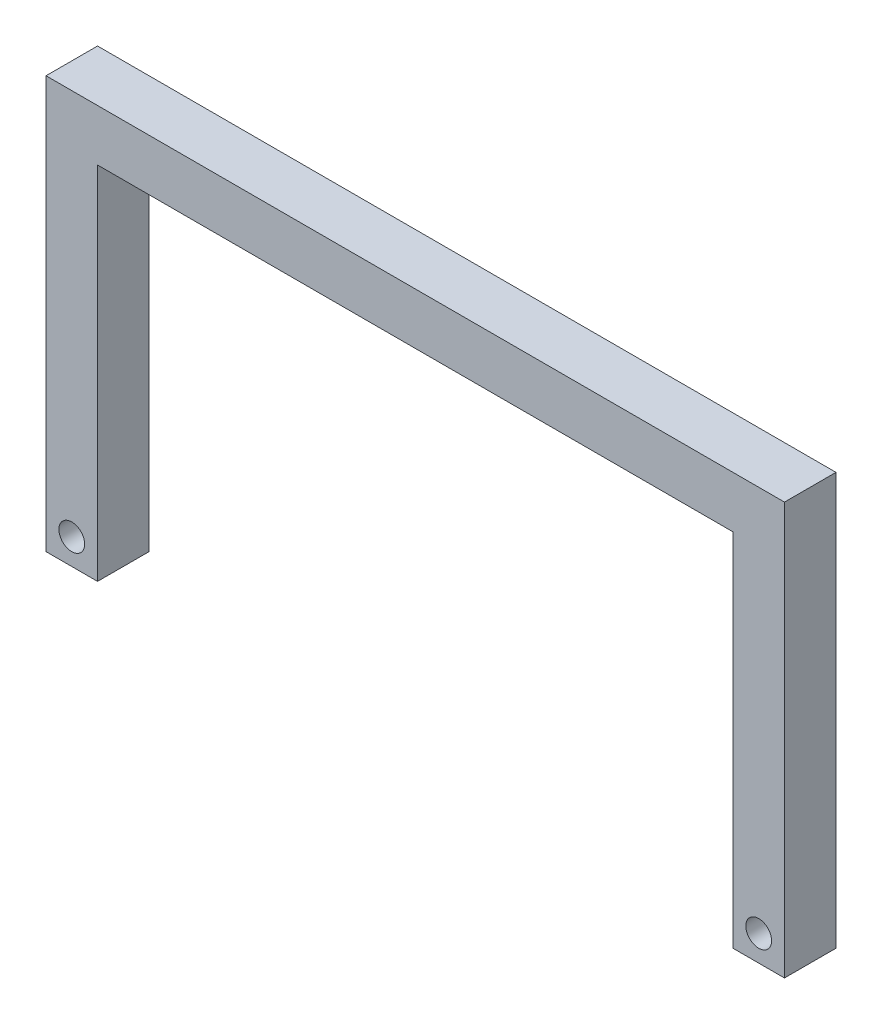
SolidWorks part; units mm, degrees
ref_plane "Front Plane" through (0, 0, 0) normal (0, 0, 1) x (1, 0, 0)
ref_plane "Top Plane" through (0, 0, 0) normal (0, 1, 0) x (1, 0, 0)
ref_plane "Right Plane" through (0, 0, 0) normal (1, 0, 0) x (0, 0, -1)
sketch "Sketch1" plane through (0, 0, 0) normal (0, 0, 1) x (1, 0, 0)
  line L0 (-185, -15) -> (-185, -225)
  line L1 (215, 15) -> (-215, 15)
  line L2 (215, 15) -> (215, -15)
  line L4 (-215, 15) -> (-215, -15)
  line L5 (215, 15) -> (-215, -15) construction
  line L6 (215, -15) -> (-215, 15) construction
  line L8 (-215, 15) -> (-215, -225)
  line L9 (-215, -225) -> (-185, -225)
  line L12 (215, 15) -> (215, -225)
  line L13 (215, -225) -> (185, -225)
  line L15 (185, -15) -> (185, -225)
  line L16 (185, -15) -> (-185, -15)
  circle A0 centre (-200, -210) radius 7.5
  circle A1 centre (200, -210) radius 7.5
  point P0 (0, 0)
  point P8 (215, 15)
  point P14 (0, 0)
  point P17 (-200, -225)
  point P18 (0, 0)
  point P19 (200, -225)
  point P20 (0, 0)
  point P21 (0, 0)
  point P23 (-16.8581, -27.3525)
  point P25 (234.8734, -59.1062)
  point P26 (184.5843, -37.122)
  point P27 (-185, -5.2158)
  point P28 (-92.7438, 15)
  point P29 (-356.1422, 15)
  point P30 (274.8308, 15)
  dimension "D2" = 15
  dimension "D1" = 30
  dimension "D4" = 15
  dimension "D5" = 400
  dimension "D3" = 240
extrude "Boss-Extrude1" add sketch "Sketch1" along normal mid plane 30 contours L16 L15 L13 L12 L2 L1 L4 L8 L9 L0 A1 A0
equation "\"table_height\"=50"
equation "\"A\"= 200"
equation "\"r6\"=400"
equation "\"D5@Sketch1\"=\"r6\""
equation "\"h6\"=240"
equation "\"D3@Sketch1\"=\"h6\""
